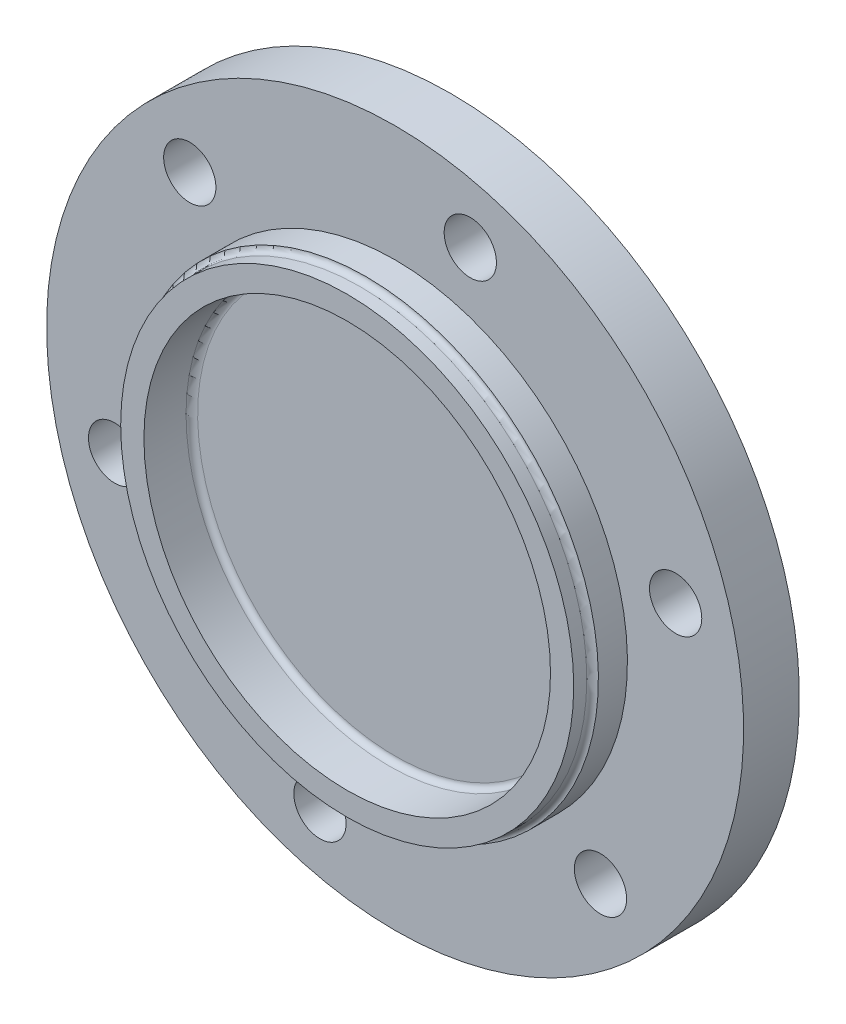
SolidWorks part; units mm, degrees
material "EN-GJL-300"
ref_plane "Front Plane" through (0, 0, 0) normal (0, 0, 1) x (1, 0, 0)
ref_plane "Top Plane" through (0, 0, 0) normal (0, 1, 0) x (1, 0, 0)
ref_plane "Right Plane" through (0, 0, 0) normal (1, 0, 0) x (0, 0, -1)
sketch "Sketch1" plane through (0, 0, 0) normal (1, 0, 0) x (0, 0, -1)
  line L0 (0, 0) -> (0, 34)
  line L1 (-1, 35) -> (-8.25, 35)
  line L2 (-8.25, 35) -> (-8.25, 39)
  line L3 (-5, 40) -> (0, 40)
  line L4 (0, 40) -> (0, 60)
  line L5 (0, 60) -> (9.6, 60)
  line L6 (9.6, 60) -> (9.6, 40)
  line L8 (7.6, 38) -> (7.6, 0)
  line L9 (7.6, 0) -> (0, 0)
  line L10 (9.6, 0) -> (-8.25, 0) construction
  line L11 (-8.25, 39) -> (-6, 39)
  line L12 (9.6, 40) -> (7.6, 38)
  arc A0 (-6, 39) -> (-5, 40) centre (-6, 40) ccw
  arc A2 (0, 34) -> (-1, 35) centre (-1, 34) ccw
  point P23 (0, 35)
  dimension "D3" = 1
  dimension "D10" = 1
  dimension "D6" = 2
  dimension "D2" = 40
  dimension "D4" = 35
  dimension "D5" = 2
  dimension "D7" = 9.6
  dimension "D8" = 60
  dimension "D9" = 5
  dimension "D11" = 8.25
revolve "Revolve1" add sketch "Sketch1" angle 360 about L10
hole_wizard "M8 Clearance Hole1" positions "Sketch2" profile "Sketch3" hole size "M8" standard "ISO" end condition up to next
sketch "Sketch2" plane through (0, 0, -9.6) normal (0, 0, -1) x (-1, 0, 0)
  line L0 (35.3553, 35.3553) -> (0, 0) construction
  line L3 (0, 50) -> (0, 0) construction
  circle A0 centre (0, 0) radius 50 construction
  point P0 (35.3553, 35.3553)
  dimension "D1" = 100
  dimension "D2" = 45
sketch "Sketch3" plane through (-35.3553, 35.3553, -9.6) normal (1, 0, 0) x (0, 1, 0)
  line L0 (0, 0) -> (0, 9.6)
  line L1 (0, 9.6) -> (4.5, 9.6)
  line L2 (4.5, 9.6) -> (4.5, 0)
  line L5 (4.5, 0) -> (0, 0)
  line L11 (0, -6.35) -> (0, 107.95) construction
  dimension "Thru Hole Dia." = 9
  dimension "Thru Hole Depth" = 9.6
pattern_circular "CirPattern1" count 6 over 360 about axis through (0, 0, 0) along (0, 0, 1) of "M8 Clearance Hole1"
equation "\"D.r\"= 52"
